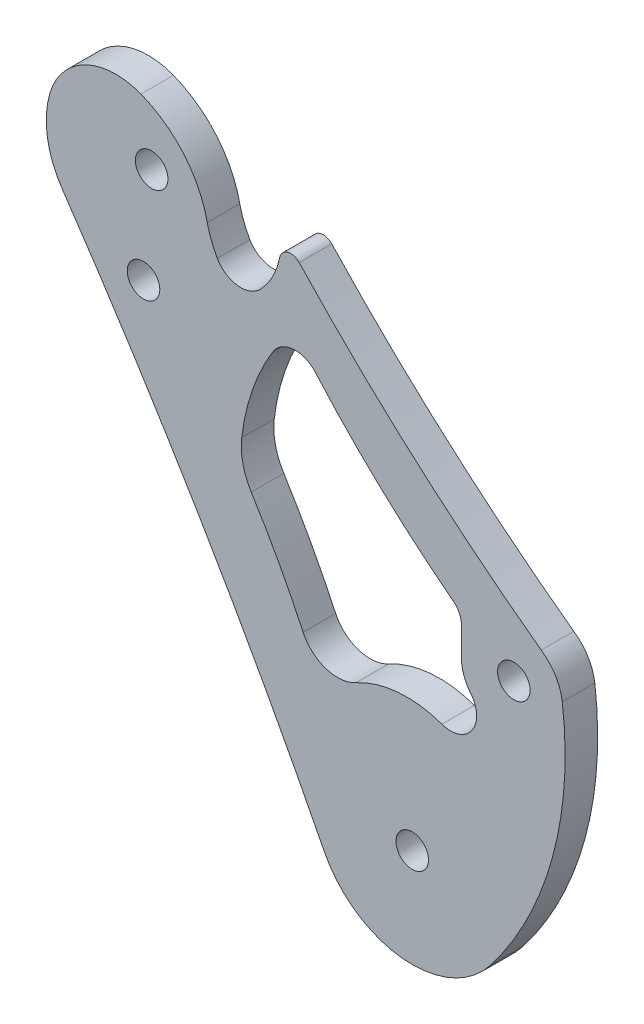
SolidWorks part; units mm, degrees
ref_plane "Plan de face" through (0, 0, 0) normal (0, 0, 1) x (1, 0, 0)
ref_plane "Plan de dessus" through (0, 0, 0) normal (0, 1, 0) x (1, 0, 0)
ref_plane "Plan de droite" through (0, 0, 0) normal (1, 0, 0) x (0, 0, -1)
sketch "Esquisse1" plane through (0, 0, 0) normal (0, 0, 1) x (1, 0, 0)
  line L0 (73.4009, 459.4032) -> (81.5095, 453.5509) construction
  line L1 (96.8497, 30.849) -> (96.8497, 33.4747)
  circle A1 centre (68.2855, 55.5604) radius 1.5
  circle A2 centre (101.6821, 31.4335) radius 1.5
  circle A3 centre (92.3124, 13.2001) radius 1.5
  circle A4 centre (67.5355, 46.3604) radius 1.5011
  arc A6 (60.0269, 49.9216) -> (84.1953, 9.0864) centre (-239.9507, -155.19) cw
  arc A7 (84.1953, 9.0864) -> (99.5091, 7.6308) centre (92.3124, 13.2001) ccw
  arc A8 (99.5091, 7.6308) -> (106.1459, 32.003) centre (73.4112, 27.8273) ccw
  arc A9 (106.1459, 32.003) -> (104.2103, 35.1562) centre (101.6821, 31.4335) ccw
  arc A11 (77.4672, 34.4096) -> (82.254, 25.6053) centre (6.216, -10.033) cw
  arc A12 (82.254, 25.6053) -> (87.1342, 24.0178) centre (85.4377, 27.0974) ccw
  arc A13 (87.1342, 24.0178) -> (95.0512, 24.6624) centre (91.8101, 15.5295) cw
  arc A14 (95.0512, 24.6624) -> (97.7092, 28.4438) centre (95.8535, 26.9233) ccw
  arc A15 (97.7092, 28.4438) -> (96.8497, 30.849) centre (100.6448, 30.849) cw
  arc A16 (96.8497, 33.4747) -> (96.0818, 35.0326) centre (94.8854, 33.4747) ccw
  arc A17 (96.0818, 35.0326) -> (83.3729, 46.9299) centre (150.5127, 105.913) cw
  arc A18 (83.3729, 46.9299) -> (79.4458, 46.5889) centre (81.5348, 45.315) ccw
  arc A19 (79.4458, 46.5889) -> (76.5917, 38.3167) centre (96.9244, 35.93) ccw
  arc A20 (76.5917, 38.3167) -> (77.4672, 34.4096) centre (82.6003, 37.6114) ccw
  arc A21 (74.9462, 53.0521) -> (69.969, 62.4758) centre (68.2855, 55.5604) ccw construction
  arc A22 (77.4672, 52.4638) -> (70.5815, 64.9743) centre (68.2855, 55.5604) ccw construction
  arc A23 (60.0269, 49.9216) -> (58.8919, 56.9478) centre (66.9298, 54.6414) cw
  arc A24 (58.8919, 56.9478) -> (67.2916, 61.1038) centre (64.985, 55.1994) cw
  arc A25 (67.2916, 61.1038) -> (73.413, 53.9091) centre (63.663, 51.8151) cw
  arc A26 (73.413, 53.9091) -> (74.3377, 51.5052) centre (81.5329, 55.653) ccw
  arc A27 (74.3377, 51.5052) -> (78.3015, 51.0166) centre (76.5036, 52.7538) ccw
  arc A28 (78.3015, 51.0166) -> (80.0855, 54.43) centre (73.4029, 55.7497) ccw
  arc A29 (80.0855, 54.43) -> (81.8892, 54.9461) centre (81.1196, 54.2258) cw
  arc A30 (81.8892, 54.9461) -> (104.2103, 35.1562) centre (199.0673, 164.6287) ccw
  dimension "D2" = 3
  dimension "D8" = 2.5
  dimension "D9" = 363.3969
  dimension "D10" = 9.1
  dimension "D11" = 33
  dimension "D12" = 4.5
  dimension "D1" = 10
  dimension "D3" = 41.2
  dimension "D4" = 48.7
  dimension "D5" = 20.5
  dimension "D6" = 9.2
  dimension "D7" = 0.75
extrude "Boss.-Extru.1" add sketch "Esquisse1" along normal blind 3
